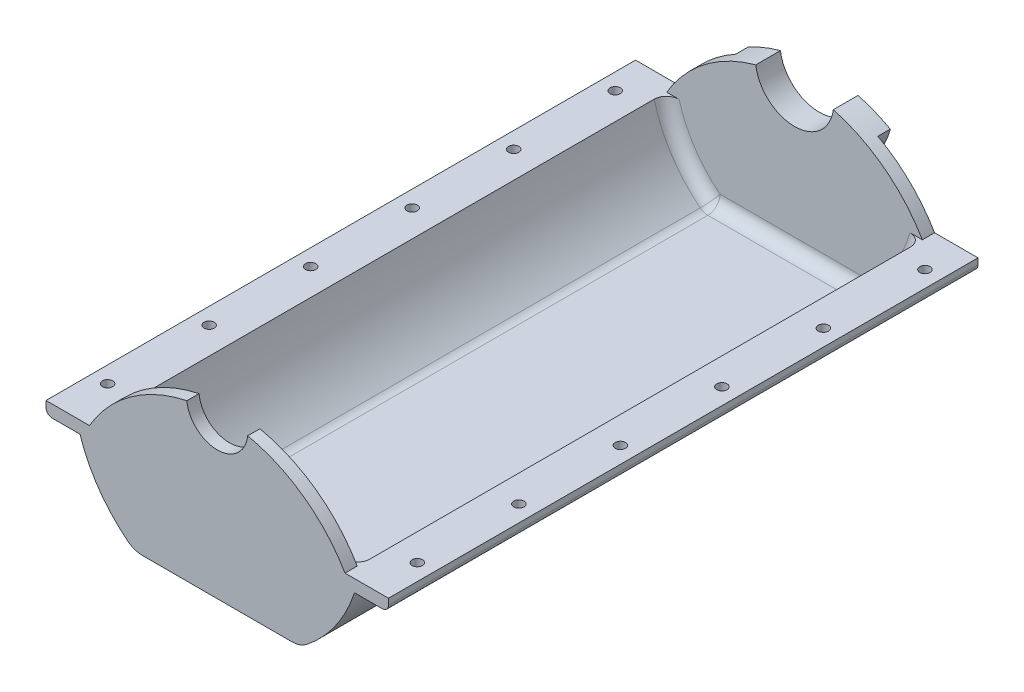
SolidWorks part; units mm, degrees
ref_plane "Alzado" through (0, 0, 0) normal (0, 0, 1) x (1, 0, 0)
ref_plane "Planta" through (0, 0, 0) normal (0, 1, 0) x (1, 0, 0)
ref_plane "Vista lateral" through (0, 0, 0) normal (1, 0, 0) x (0, 0, -1)
sketch "Croquis1" plane through (0, 0, 0) normal (0, 0, 1) x (1, 0, 0)
  line L0 (0, 0) -> (230, 0)
  line L1 (54.1088, -70.3485) -> (175.8912, -70.3485)
  arc A0 (0, 0) -> (41.6821, -66.0194) centre (115, 26.4386) ccw
  arc A1 (188.3179, -66.0194) -> (230, 0) centre (115, 26.4386) ccw
  arc A2 (175.8912, -70.3485) -> (188.3179, -66.0194) centre (175.8912, -50.3485) ccw
  arc A3 (54.1088, -70.3485) -> (41.6821, -66.0194) centre (54.1088, -50.3485) cw
  point P7 (115, -70.3485)
  point P8 (115, 0)
  point P11 (182.5, -70.3485)
  point P14 (47.5, -70.3485)
  dimension "D2" = 118
  dimension "D4" = 20
  dimension "D1" = 230
  dimension "D3" = 135
extrude "Saliente-Extruir1" add sketch "Croquis1" along normal blind 482
shell "Vaciado1" thickness 10
fillet "Redondeo1" radius 10 5 edges at (24.2986, -32.1896, 472) (50.819, -59.7919, 472) (205.7014, -32.1896, 472) (179.181, -59.7919, 472) (115, -60.3485, 472)
fillet "Redondeo2" radius 10 5 edges at (24.2986, -32.1896, 10) (50.819, -59.7919, 10) (205.7014, -32.1896, 10) (179.181, -59.7919, 10) (115, -60.3485, 10)
sketch "Croquis2" plane through (0, 0, 482) normal (0, 0, 1) x (1, 0, 0)
  line L0 (2.7671, -10) -> (-25.0029, -10)
  line L1 (-25.0029, -10) -> (-25.0029, 0)
  line L2 (-25.0029, 0) -> (0, 0)
  line L3 (115, -70.3485) -> (115, -9.8963) construction
  line L4 (54.1088, -70.3485) -> (175.8912, -70.3485) construction
  line L5 (255.0029, 0) -> (230, 0)
  line L6 (255.0029, -10) -> (255.0029, 0)
  line L7 (227.2329, -10) -> (255.0029, -10)
  arc A0 (0, 0) -> (41.6821, -66.0194) centre (115, 26.4386) ccw construction
  arc A1 (0, 0) -> (2.7671, -10) centre (115, 26.4386) ccw
  arc A2 (230, 0) -> (227.2329, -10) centre (115, 26.4386) cw
  dimension "D1" = 10
  dimension "D2" = 25.0029
extrude "Saliente-Extruir2" add sketch "Croquis2" against normal blind 482
fillet "Redondeo3" radius 5 2 edges at (255.0029, -10, 241) (-25.0029, -10, 241)
sketch "Croquis3" plane through (0, 0, 0) normal (0, 0, -1) x (-1, 0, 0)
  line L0 (-115, 0) -> (-115, 60) construction
  line L1 (-255.0029, 0) -> (25.0029, 0) construction
  line L2 (-10.515, 0) -> (-219.485, 0)
  line L3 (-209.3663, 0) -> (-20.6337, 0) construction
  arc A0 (-219.485, 0) -> (-146.7189, 55.7678) centre (-115, -60.976) cw
  arc A2 (-146.7189, 55.7678) -> (-83.2811, 55.7678) centre (-115, 60) ccw
  arc A3 (-83.2811, 55.7678) -> (-10.515, 0) centre (-115, -60.976) cw
  point P7 (-115, 0)
  dimension "D3" = 64
  dimension "D1" = 60
  dimension "D2" = 208.97
  dimension "D5" = 63.4378
extrude "Saliente-Extruir3" add sketch "Croquis3" against normal blind 10 separate body
sketch "Croquis4" plane through (0, 0, 0) normal (0, 0, -1) x (-1, 0, 0)
  arc A0 (-173.1259, 45.121) -> (-56.8741, 45.121) centre (-115, 60) ccw
  arc A1 (-10.515, 0) -> (-83.2811, 55.7678) centre (-115, -60.976) ccw construction
  arc A2 (-146.7189, 55.7678) -> (-83.2811, 55.7678) centre (-115, 60) ccw construction
  arc A3 (-146.7189, 55.7678) -> (-219.485, 0) centre (-115, -60.976) ccw construction
  arc A4 (-56.8741, 45.121) -> (-83.2811, 55.7678) centre (-115, -60.976) ccw
  arc A5 (-146.7189, 55.7678) -> (-83.2811, 55.7678) centre (-115, 60) ccw
  arc A6 (-146.7189, 55.7678) -> (-173.1259, 45.121) centre (-115, -60.976) ccw
  dimension "D1" = 120
extrude "Saliente-Extruir4" add sketch "Croquis4" along normal blind 10.2
sketch "Croquis5" plane through (0, 0, 482) normal (0, 0, 1) x (1, 0, 0)
  line L1 (10.515, 0) -> (219.485, 0)
  line L2 (10.515, 0) -> (219.485, 0)
  arc A0 (90.1338, 57.4168) -> (139.8662, 57.4168) centre (115, 60) ccw
  arc A1 (10.515, 0) -> (90.1338, 57.4168) centre (115, -60.976) cw
  arc A2 (139.8662, 57.4168) -> (219.485, 0) centre (115, -60.976) cw
  arc A3 (219.485, 0) -> (146.7189, 55.7678) centre (115, -60.976) ccw
  arc A4 (83.2811, 55.7678) -> (146.7189, 55.7678) centre (115, 60) ccw
  arc A5 (83.2811, 55.7678) -> (10.515, 0) centre (115, -60.976) ccw
  arc A6 (219.485, 0) -> (146.7189, 55.7678) centre (115, -60.976) ccw
  arc A7 (83.2811, 55.7678) -> (146.7189, 55.7678) centre (115, 60) ccw construction
  arc A8 (83.2811, 55.7678) -> (10.515, 0) centre (115, -60.976) ccw
  line M8 (255.0029, 0) -> (-25.0029, 0)
  dimension "D2" = 50
  dimension "D3" = 49.7324
  dimension "D1" = 0
extrude "Saliente-Extruir5" add sketch "Croquis5" against normal blind 10 contours A2 A0 A1 M8
sketch "Croquis6" plane through (0, 0, 0) normal (0, 1, 0) x (1, 0, 0)
  line L0 (-25.0029, 0) -> (-25.0029, -482) construction
  line L1 (10.515, 0) -> (-25.0029, 0) construction
  point P0 (-11.6229, -30)
  point P7 (-11.6229, -113)
  point P8 (-11.6229, -196)
  point P9 (-11.6229, -279)
  point P10 (-11.6229, -362)
  point P11 (-11.6229, -445)
  dimension "D1" = 30
  dimension "D3" = 83
  dimension "D4" = 13.38
  dimension "D2" = 6
hole_wizard "Ranura de margen para M81" positions "Croquis7" profile "Croquis8" size "M8" standard "Ansi Metric" slot yes
sketch "Croquis7" plane through (0, 0, 0) normal (0, 1, 0) x (1, 0, 0)
  point P0 (-11.6229, -30)
  point P3 (-11.6229, -113)
  point P6 (-11.6229, -196)
  point P9 (-11.6229, -279)
  point P12 (-11.6229, -362)
  point P15 (-11.6229, -445)
sketch "Croquis8" plane through (-11.6229, 0, 30) normal (1, 0, 0) x (0, 0, 1)
  line L0 (0, 0) -> (0, 92.5236)
  line L1 (0, 92.5236) -> (4.2, 90)
  line L2 (4.2, 90) -> (4.2, 0)
  line L5 (4.2, 0) -> (0, 0)
  line L10 (0, 92.5236) -> (-4.2, 90) construction
  line L11 (0, -6.35) -> (0, 107.95) construction
  dimension "Diámetro de taladro" = 8.4
  dimension "Profundidad de taladro" = 90
  dimension "Ángulo de perforador" = 118
sketch "Croquis9" plane through (0, 0, 482) normal (0, 0, 1) x (1, 0, 0)
  line L0 (115, 35) -> (115, -70.3485)
  line L1 (54.1088, -70.3485) -> (175.8912, -70.3485) construction
  arc A0 (90.1338, 57.4168) -> (139.8662, 57.4168) centre (115, 60) ccw construction
ref_plane "Plano1" through (115, 0, 0) normal (1, 0, 0) x (0, 0, -1)
mirror "Simetría1" about plane through (115, 0, 0) normal (1, 0, 0) of "Ranura de margen para M81"
